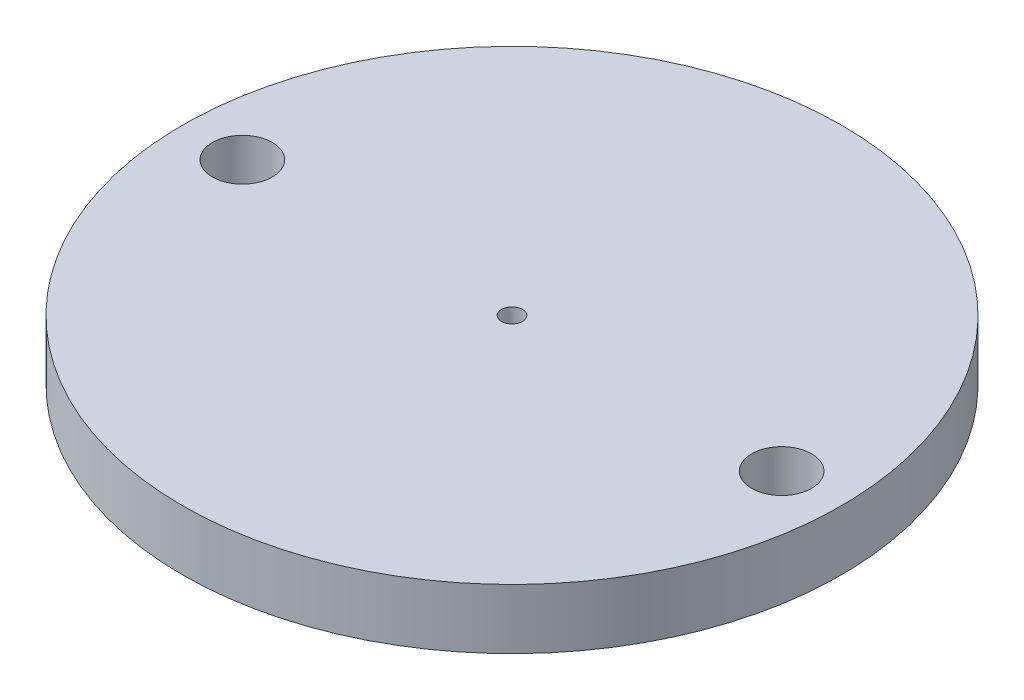
SolidWorks part; units mm, degrees
ref_plane "Front Plane" through (0, 0, 0) normal (0, 0, 1) x (1, 0, 0)
ref_plane "Top Plane" through (0, 0, 0) normal (0, 1, 0) x (1, 0, 0)
ref_plane "Right Plane" through (0, 0, 0) normal (1, 0, 0) x (0, 0, -1)
sketch "Sketch1" plane through (0, 0, 0) normal (0, 1, 0) x (1, 0, 0)
  line L0 (0, -55) -> (0, 55) construction
  circle A0 centre (0, 0) radius 55
  circle A1 centre (0, 0) radius 1.75
  circle A2 centre (-45, 0) radius 5
  circle A3 centre (45, 0) radius 5
  dimension "D1" = 110
  dimension "D2" = 3.5
  dimension "D3" = 10
  dimension "D4" = 45
extrude "Boss-Extrude1" add sketch "Sketch1" along normal blind 10
